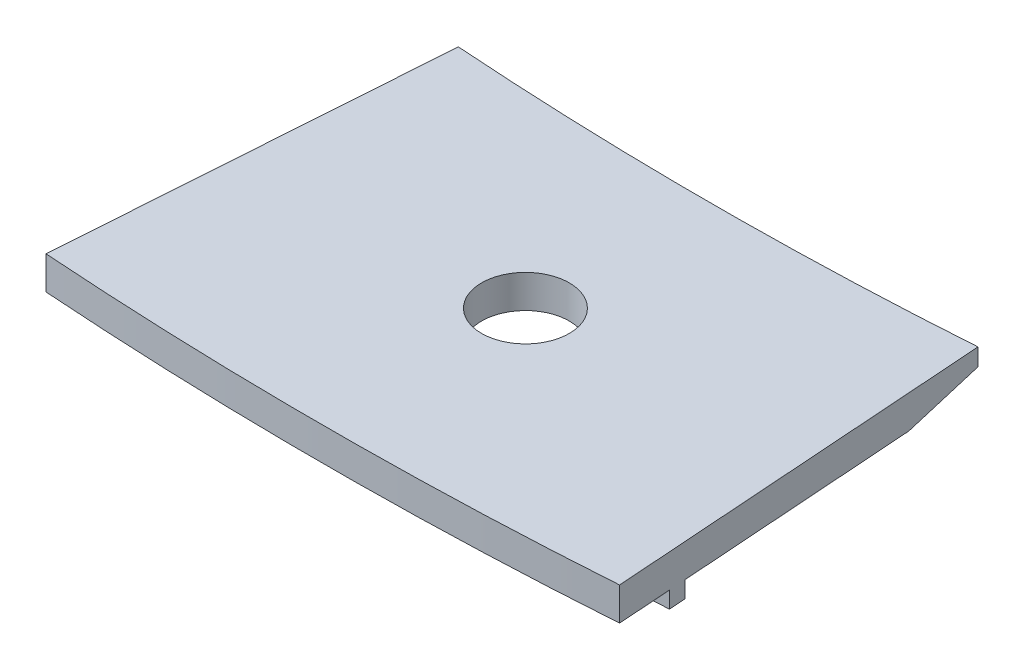
SolidWorks part; units mm, degrees
ref_plane "Front Plane" through (0, 0, 0) normal (0, 0, 1) x (1, 0, 0)
ref_plane "Top Plane" through (0, 0, 0) normal (0, 1, 0) x (1, 0, 0)
ref_plane "Right Plane" through (0, 0, 0) normal (1, 0, 0) x (0, 0, -1)
sketch "BASE" plane through (0, 0, 0) normal (0, 1, 0) x (1, 0, 0)
  line L0 (0, 0) -> (0, -243.5) construction
  line L1 (15.9742, -228.4422) -> (16.9857, -242.9068)
  line L2 (-15.9742, -228.4422) -> (-16.9857, -242.9068)
  line L3 (0, 0) -> (15.9742, -228.4422) construction
  line L4 (0, 0) -> (-15.9742, -228.4422) construction
  line L5 (0, -229) -> (0, -243.5) construction
  line L7 (-10, -226.25) -> (10, -226.25) construction
  line L8 (-10, -226.25) -> (-10, -246.25) construction
  line L9 (-10, -246.25) -> (10, -246.25) construction
  line L10 (10, -226.25) -> (10, -246.25) construction
  line L11 (-10, -226.25) -> (10, -246.25) construction
  line L12 (-10, -246.25) -> (10, -226.25) construction
  arc A0 (-16.9857, -242.9068) -> (16.9857, -242.9068) centre (0, 0) ccw
  arc A1 (-15.9742, -228.4422) -> (15.9742, -228.4422) centre (0, 0) ccw
  circle A2 centre (0, -236.25) radius 2.65
  dimension "D1" = 487
  dimension "D2" = 14.5
  dimension "D6" = 5.3
  dimension "D3" = 4
  dimension "D4" = 4
  dimension "D5" = 20
sketch "Sketch2" plane through (0, 0, 0) normal (0, 1, 0) x (1, 0, 0)
  line L1 (-15.9742, -228.4422) -> (-16.9857, -242.9068) construction
  line L3 (15.9742, -228.4422) -> (16.9857, -242.9068) construction
  line L4 (0, 0) -> (-17.3345, -247.8947) construction
  line L5 (0, 0) -> (17.3345, -247.8947) construction
  line L6 (-15.9847, -228.5918) -> (-17.3345, -247.8947)
  line L7 (15.9847, -228.5918) -> (17.3345, -247.8947)
  arc A0 (15.9847, -228.5918) -> (-15.9847, -228.5918) centre (0, 0) cw
  arc A1 (-15.9742, -228.4422) -> (15.9742, -228.4422) centre (0, 0) ccw construction
  arc A2 (17.3345, -247.8947) -> (-17.3345, -247.8947) centre (0, 0) cw
  arc A3 (-16.9857, -242.9068) -> (16.9857, -242.9068) centre (0, 0) ccw construction
  circle A4 centre (0, -236.25) radius 2.65
  dimension "D1" = 0.15
  dimension "D2" = 5
  dimension "D3" = 5.3
extrude "Boss-Extrude1" add sketch "Sketch2" along normal blind 2
sketch "Sketch3" plane through (0, 0, 0) normal (0, 1, 0) x (1, 0, 0)
  line L0 (0, 0) -> (15.9742, -228.4422) construction
  line L1 (0, 0) -> (-15.9742, -228.4422) construction
  line L2 (-15.7057, -224.6015) -> (-15.9847, -228.5918)
  line L3 (15.7057, -224.6015) -> (15.9847, -228.5918)
  arc A0 (15.9847, -228.5918) -> (-15.9847, -228.5918) centre (0, 0) cw
  arc A1 (15.7057, -224.6015) -> (-15.7057, -224.6015) centre (0, 0) cw
  dimension "D1" = 4
extrude "Boss-Extrude2" add sketch "Sketch3" against normal blind 2 from surface at 2 starting at face at (0, 2, 238.5341)
chamfer "Chamfer1" distance 4.5 angle 12 1 edges at (0, 0, 225.15)
sketch "Sketch4" plane through (0, 0, 0) normal (0, -1, 0) x (1, 0, 0)
  line L0 (15.9742, 228.4422) -> (16.9857, 242.9068) construction
  line L1 (-16.0196, 229.0906) -> (-17.3345, 247.8947) construction
  line L2 (17.3345, 247.8947) -> (16.0196, 229.0906) construction
  line L3 (-17.1079, 244.655) -> (-17.038, 243.655)
  line L4 (17.1079, 244.655) -> (17.038, 243.655)
  arc A0 (-17.038, 243.655) -> (17.038, 243.655) centre (0, 0) cw
  arc A1 (-17.1079, 244.655) -> (17.1079, 244.655) centre (0, 0) cw
  arc A2 (16.9857, 242.9068) -> (-16.9857, 242.9068) centre (0, 0) ccw construction
  point P13 (0, 0)
  dimension "D2" = 0.75
  dimension "D1" = 1
extrude "Boss-Extrude3" add sketch "Sketch4" along normal blind 1
